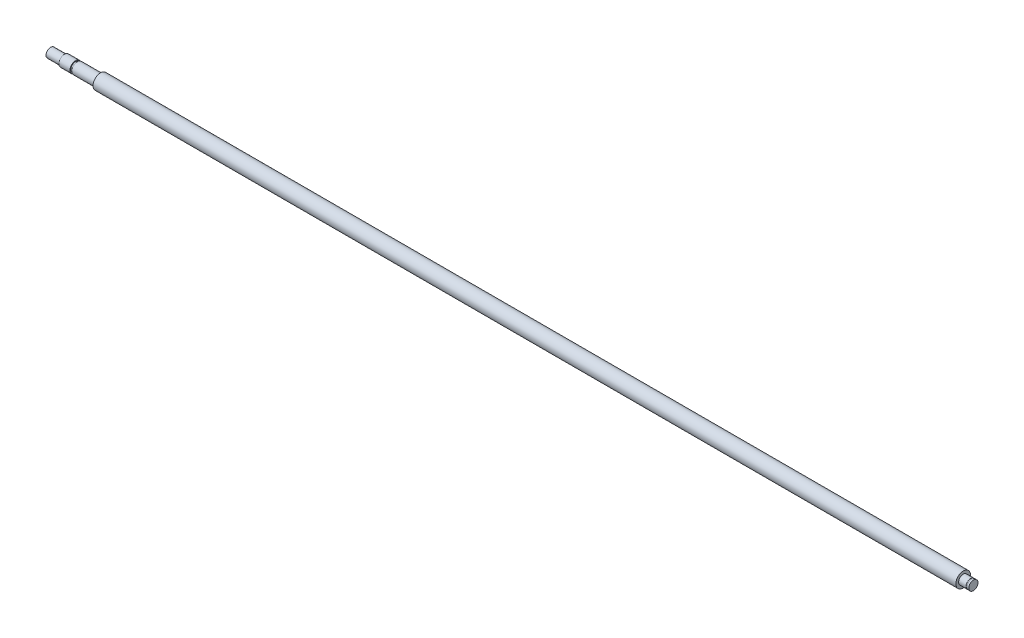
SolidWorks part; units mm, degrees
material "Plain Carbon Steel"
ref_plane "Front Plane" through (0, 0, 0) normal (0, 0, 1) x (1, 0, 0)
ref_plane "Top Plane" through (0, 0, 0) normal (0, 1, 0) x (1, 0, 0)
ref_plane "Right Plane" through (0, 0, 0) normal (1, 0, 0) x (0, 0, -1)
sketch "Sketch1" plane through (0, 0, 0) normal (0, 0, 1) x (1, 0, 0)
  line L0 (-54, 0) -> (946, 0)
  line L1 (946, 0) -> (946, 5)
  line L2 (946, 5) -> (944.15, 5)
  line L3 (944.15, 5) -> (944.15, 4.8)
  line L4 (944.15, 4.8) -> (943, 4.8)
  line L5 (943, 4.8) -> (943, 5)
  line L6 (943, 5) -> (935, 5)
  line L7 (935, 5) -> (935, 8)
  line L8 (935, 8) -> (0, 8)
  line L9 (0, 8) -> (0, 6)
  line L10 (0, 6) -> (-25, 6)
  line L11 (-25, 6) -> (-25, 5)
  line L12 (-25, 5) -> (-27, 5)
  line L13 (-27, 5) -> (-27, 6)
  line L14 (-27, 6) -> (-39, 6)
  line L15 (-39, 6) -> (-39, 5)
  line L16 (-39, 5) -> (-54, 5)
  line L17 (-54, 5) -> (-54, 0)
  point P18 (467.5, 8)
  dimension "D1" = 2
  dimension "D2" = 15
  dimension "D3" = 14
  dimension "D4" = 39
  dimension "D5" = 1.15
  dimension "D6" = 0.2
  dimension "D7" = 8
  dimension "D8" = 11
  dimension "D9" = 1000
  dimension "D10" = 5
  dimension "D11" = 6
  dimension "D12" = 8
revolve "Revolve1" add sketch "Sketch1" angle 360 about L0
